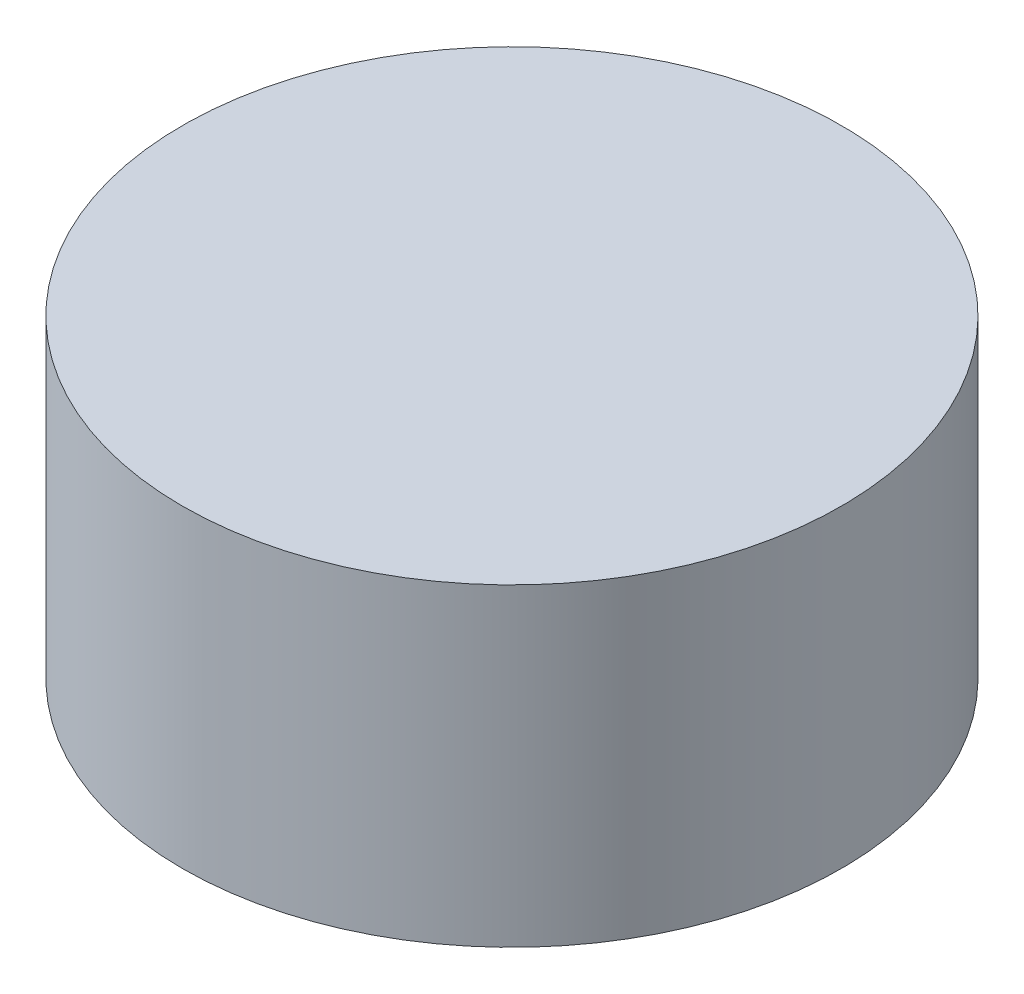
SolidWorks part; units mm, degrees
ref_plane "Front Plane" through (0, 0, 0) normal (0, 0, 1) x (1, 0, 0)
ref_plane "Top Plane" through (0, 0, 0) normal (0, 1, 0) x (1, 0, 0)
ref_plane "Right Plane" through (0, 0, 0) normal (1, 0, 0) x (0, 0, -1)
sketch "Sketch1" plane through (0, 0, 0) normal (0, 1, 0) x (1, 0, 0)
  circle A0 centre (0, 0) radius 10.5
extrude "Boss-Extrude1" add sketch "Sketch1" along normal blind 10
